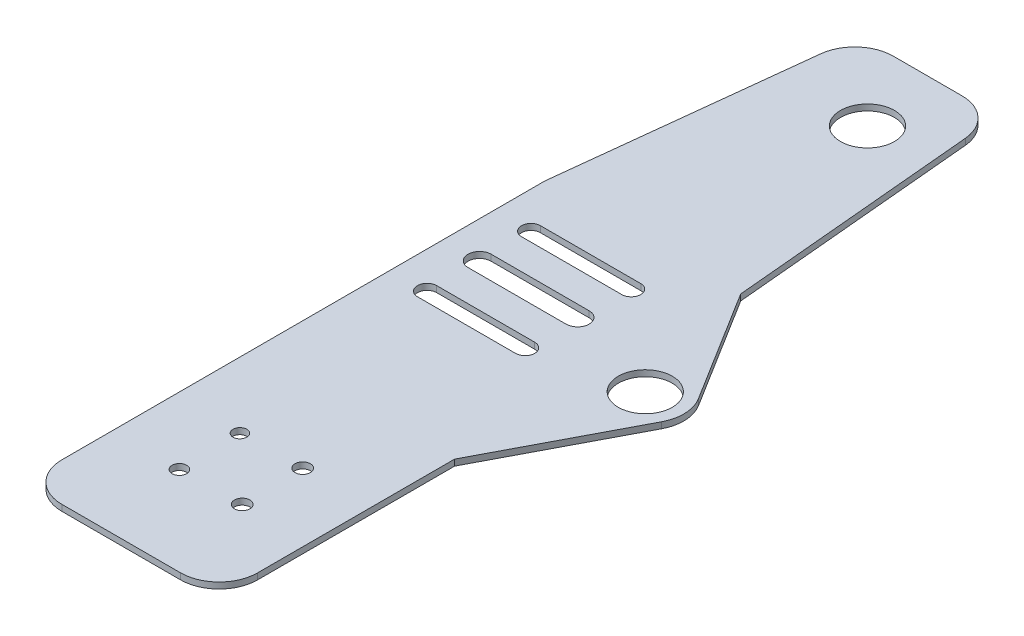
SolidWorks part; units mm, degrees
ref_plane "Front" through (0, 0, 0) normal (0, 0, 1) x (1, 0, 0)
ref_plane "Top" through (0, 0, 0) normal (0, 1, 0) x (1, 0, 0)
ref_plane "Right" through (0, 0, 0) normal (1, 0, 0) x (0, 0, -1)
sketch "Sketch1" plane through (0, 0, 0) normal (0, 1, 0) x (1, 0, 0)
  line L0 (10.4543, 228.6) -> (0, 135.3627)
  line L1 (0, 0) -> (50.8, 0)
  line L2 (0, 0) -> (0, 228.6)
  line L3 (0, 228.6) -> (50.8, 228.6)
  line L4 (50.8, 0) -> (50.8, 228.6)
  line L5 (42.3273, 228.6) -> (50.8, 135.3627)
  line L8 (50.8, 0) -> (24.327, 0)
  line L9 (50.8, 0) -> (50.8, -15)
  line L10 (50.8, -15) -> (24.327, -15)
  line L11 (24.327, 0) -> (24.327, -15)
  line L16 (50.8, 120.6192) -> (50.8, 104.4882)
  line L18 (50.8, 64.8791) -> (50.8, 87.4235)
  line L20 (9.492, 92.7849) -> (34.9257, 92.7849)
  line L21 (9.492, 92.7849) -> (9.492, 97.7849)
  line L22 (9.492, 97.7849) -> (34.9257, 97.7849)
  line L23 (34.9257, 92.7849) -> (34.9257, 97.7849)
  line L25 (9.492, 105.9099) -> (34.9257, 105.9099)
  line L26 (9.492, 105.9099) -> (9.492, 111.9099)
  line L27 (9.492, 111.9099) -> (34.9257, 111.9099)
  line L28 (34.9257, 105.9099) -> (34.9257, 111.9099)
  line L30 (9.492, 119.7849) -> (35.5097, 119.7849)
  line L31 (9.492, 119.7849) -> (9.492, 124.7158)
  line L32 (9.492, 124.7158) -> (35.5097, 124.7158)
  line L33 (35.5097, 119.7849) -> (35.5097, 124.7158)
  circle A12 centre (60.4, 101.001) radius 10
  circle A13 centre (29.5042, 189.5572) radius 7
  circle A18 centre (17.4184, 23.0817) radius 1.897
  circle A19 centre (33.4158, 23.3728) radius 2
  circle A20 centre (33.1247, 39.3701) radius 2
  circle A21 centre (17.1274, 39.0791) radius 1.786
  circle A22 centre (9.492, 95.2849) radius 2.5
  circle A23 centre (34.9257, 95.2849) radius 2.5
  circle A24 centre (34.9257, 108.9099) radius 3
  circle A25 centre (9.492, 108.9099) radius 3
  circle A26 centre (9.492, 122.2504) radius 2.4654
  circle A27 centre (35.5097, 122.2504) radius 2.4654
  dimension "D3" = 20
  dimension "D4" = 103.8842
  dimension "D5" = 15
  dimension "D6" = 14
  dimension "D7" = 116.6901
  dimension "D1" = 50.8
  dimension "D2" = 228.6
  dimension "D8" = 130.8151
extrude "Boss-Extrude1" add sketch "Sketch1" along normal blind 1.5875 contours L1 L4 L3 L0 L2
sketch "Sketch4" plane through (0, 0, -228.6) normal (0, 0, -1) x (-1, 0, 0)
  line L1 (-61.3109, 11.9192) -> (4.9615, 11.9192)
  line L2 (-61.3109, 11.9192) -> (-61.3109, -15.8811)
  line L3 (-61.3109, -15.8811) -> (4.9615, -15.8811)
  line L4 (4.9615, 11.9192) -> (4.9615, -15.8811)
extrude "Cut-Extrude2" cut sketch "Sketch4" against normal blind 20
fillet "Fillet3" radius 10 1 edges at (44.1447, 0.7937, -208.6)
fillet "Fillet4" radius 10 3 edges at (50.8, 0.7937, 0) (0, 0.7937, 0) (8.2118, 0.7937, -208.6)
sketch "Sketch6" plane through (0, 1.5875, 0) normal (0, 1, 0) x (1, 0, 0)
  line L0 (68.8909, 106.2834) -> (50.8, 135.3627)
  line L1 (50.8, 135.3627) -> (50.8, 103.801)
  line L2 (69.2582, 96.3607) -> (50.8, 61.1242)
  line L3 (50.8, 10) -> (50.8, 98.201) construction
  line L4 (50.8, 61.1242) -> (50.8, 96.3607)
  line L5 (50.8, 96.3607) -> (50.8, 98.201)
  circle A0 centre (60.4, 101.001) radius 10
extrude "Boss-Extrude3" add sketch "Sketch6" against normal blind 1.5875
sketch "Sketch7" plane through (0, 1.5875, 0) normal (0, 1, 0) x (1, 0, 0)
  circle A0 centre (60.4, 101.001) radius 7
  dimension "D1" = 14
extrude "Cut-Extrude3" cut sketch "Sketch7" against normal blind 1.5875
equation "\"7i\"=101.6"
